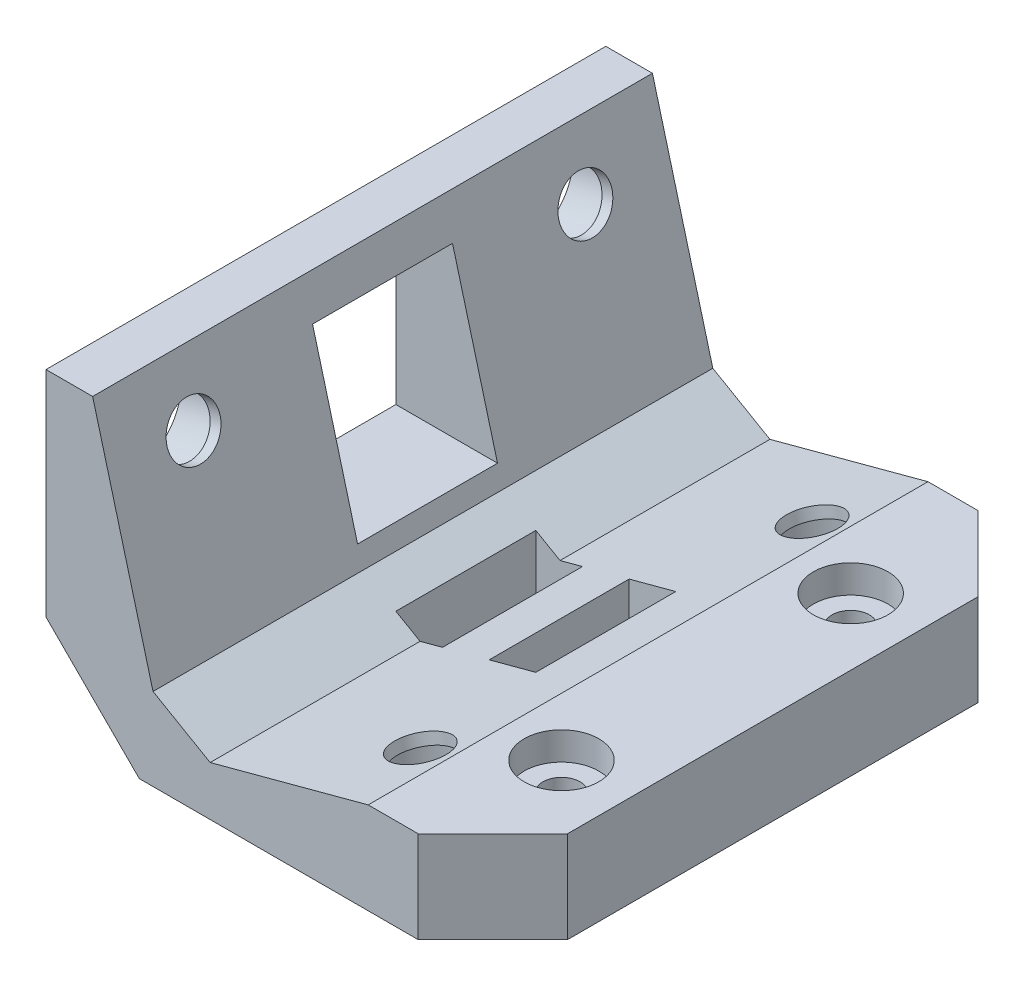
SolidWorks part; units mm, degrees
ref_plane "Plan de face" through (0, 0, 0) normal (0, 0, 1) x (1, 0, 0)
ref_plane "Plan de dessus" through (0, 0, 0) normal (0, 1, 0) x (1, 0, 0)
ref_plane "Plan de droite" through (0, 0, 0) normal (1, 0, 0) x (0, 0, -1)
sketch "Esquisse1" plane through (0, 0, 0) normal (0, 0, 1) x (1, 0, 0)
  line L0 (0, 0) -> (44.8947, 0)
  line L1 (44.8947, 0) -> (41.7423, 11.7646)
  line L2 (41.7423, 11.7646) -> (12.7646, 4)
  line L3 (12.7646, 4) -> (5, 32.9778)
  line L4 (5, 32.9778) -> (0, 32.9778)
  line L5 (0, 32.9778) -> (0, 0)
  dimension "D1" = 90
  dimension "D2" = 15
  dimension "D3" = 5
  dimension "D4" = 4
  dimension "D5" = 30
  dimension "D6" = 30
extrude "Boss.-Extru.1" add sketch "Esquisse1" along normal blind 60
sketch "Esquisse2" plane through (12.9095, 3.4591, 0) normal (0.9659, 0.2588, 0) x (0, 0, -1)
  circle A0 centre (-51, 23.56) radius 2.85
  circle A1 centre (-9, 23.56) radius 2.85
sketch "Esquisse3" plane through (-0.1449, 0.5409, 0) normal (-0.2588, 0.9659, 0) x (0.9659, 0.2588, 0)
  circle A0 centre (32.3649, -9) radius 2.85
  circle A1 centre (32.3649, -51) radius 2.85
extrude "Enlèv. mat.-Extru.1" cut sketch "Esquisse2" against normal blind 30
extrude "Enlèv. mat.-Extru.2" cut sketch "Esquisse3" against normal blind 1.2
sketch "Esquisse4" plane through (12.9095, 3.4591, 0) normal (0.9659, 0.2588, 0) x (0, 0, -1)
  circle A0 centre (-51, 23.56) radius 5.5
  circle A1 centre (-9, 23.56) radius 5.5
  dimension "D1" = 11
  dimension "D2" = 11
extrude "Enlèv. mat.-Extru.3" cut sketch "Esquisse4" against normal blind 30 from offset 1.2 offset against normal yes
chamfer "Chanfrein1" distance 5 angle 45 1 edges at (12.7646, 4, 30)
chamfer "Chanfrein3" distance 10 angle 45 1 edges at (0, 0, 30)
sketch "Esquisse7" plane through (0, 0, 0) normal (0, -1, 0) x (1, 0, 0)
  circle A0 centre (31.1172, 51) radius 5.5
  circle A1 centre (31.1172, 9) radius 5.5
  ellipse E0 centre (31.1172, 9) end of major axis (31.1172, 11.85) minor radius 2.7529 construction
  ellipse E1 centre (31.1172, 51) end of major axis (31.1172, 53.85) minor radius 2.7529 construction
  point P5 (29.1853, 9)
  dimension "D1" = 11
  dimension "D2" = 11
extrude "Enlèv. mat.-Extru.5" cut sketch "Esquisse7" against normal up to surface (9.149 mm away)
chamfer "Chanfrein4" distance 2 angle 75 1 edges at (41.7423, 11.7646, 30)
sketch "Esquisse8" plane through (0, 0, 60) normal (0, 0, 1) x (1, 0, 0)
  line L0 (42.26, 9.8327) -> (47.8947, 9.8327)
  line L1 (47.8947, 9.8327) -> (47.8947, 0)
  line L2 (47.8947, 0) -> (44.8947, 0)
  line L3 (44.8947, 0) -> (42.26, 9.8327)
  dimension "D1" = 3
extrude "Boss.-Extru.3" add sketch "Esquisse8" against normal blind 60
sketch "Esquisse10" plane through (0, 9.8327, 0) normal (0, 1, 0) x (1, 0, 0)
  circle A0 centre (40.75, -14.5) radius 2
  circle A1 centre (40.75, -45.5) radius 2
  dimension "D1" = 4
  dimension "D2" = 4
extrude "Enlèv. mat.-Extru.7" cut sketch "Esquisse10" against normal blind 60
sketch "Esquisse11" plane through (0, 9.8327, 0) normal (0, 1, 0) x (1, 0, 0)
  circle A0 centre (40.75, -14.5) radius 4
  circle A1 centre (40.75, -45.5) radius 4
  dimension "D1" = 8
  dimension "D2" = 8
extrude "Enlèv. mat.-Extru.8" cut sketch "Esquisse11" against normal blind 3
chamfer "Chanfrein5" distance 8 angle 45 2 edges at (47.8947, 4.9164, 60) (47.8947, 4.9164, 0)
sketch "Esquisse12" plane through (0, 0, 0) normal (0, -1, 0) x (1, 0, 0)
  line L0 (47.8947, 30) -> (10, 30) construction
  line L1 (15, 22.5) -> (20, 22.5)
  line L2 (15, 22.5) -> (15, 37.5)
  line L3 (15, 37.5) -> (20, 37.5)
  line L4 (20, 22.5) -> (20, 37.5)
  line L5 (25, 22.5) -> (30, 22.5)
  line L6 (25, 22.5) -> (25, 37.5)
  line L7 (25, 37.5) -> (30, 37.5)
  line L8 (30, 22.5) -> (30, 37.5)
  line L9 (47.8947, 8) -> (47.8947, 52) construction
  line L10 (10, 60) -> (10, 0) construction
  dimension "D1" = 15
  dimension "D2" = 15
  dimension "D3" = 5
  dimension "D4" = 5
  dimension "D5" = 5
  dimension "D6" = 5
extrude "Enlèv. mat.-Extru.9" cut sketch "Esquisse12" against normal through all
sketch "Esquisse13" plane through (0, 0, 0) normal (-1, 0, 0) x (0, 0, 1)
  line L0 (30, 32.9778) -> (30, 10) construction
  line L1 (22.5, 28.9778) -> (37.5, 28.9778)
  line L2 (22.5, 28.9778) -> (22.5, 10.9778)
  line L3 (22.5, 10.9778) -> (37.5, 10.9778)
  line L4 (37.5, 28.9778) -> (37.5, 10.9778)
  line L5 (60, 32.9778) -> (0, 32.9778) construction
  line L6 (0, 10) -> (60, 10) construction
  dimension "D1" = 15
  dimension "D2" = 18
  dimension "D3" = 4
extrude "Enlèv. mat.-Extru.10" cut sketch "Esquisse13" against normal through all
equation "\"6à\"=15"
